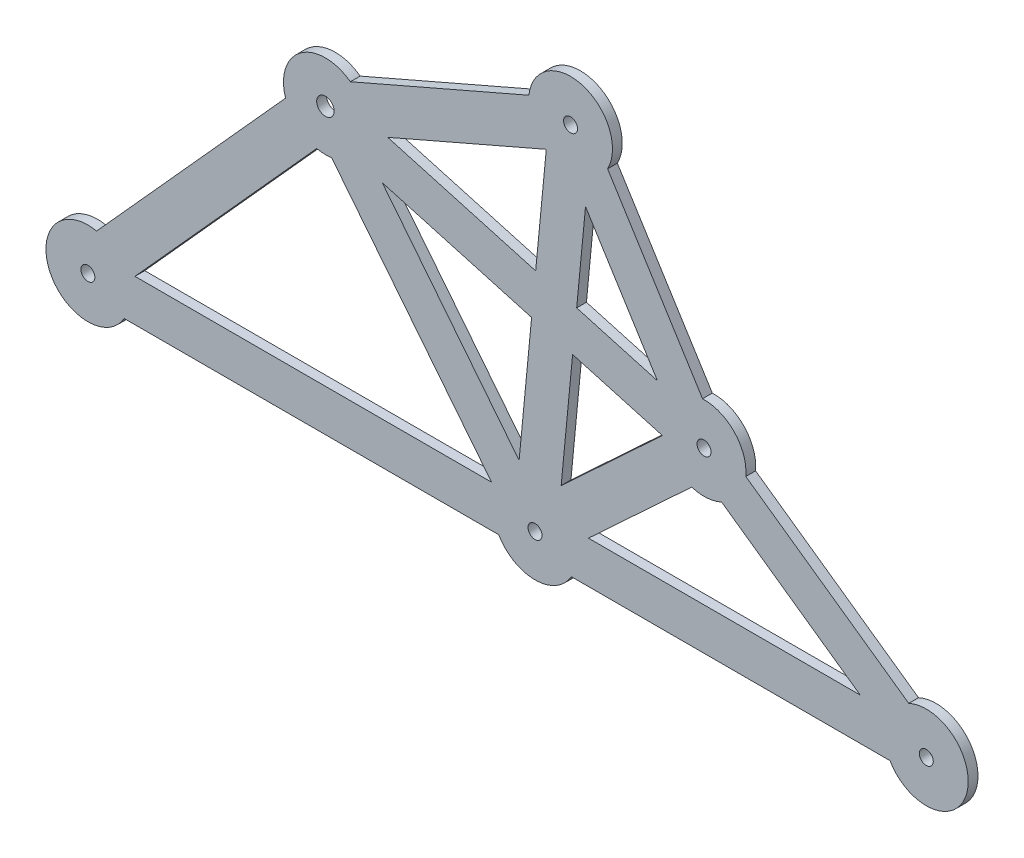
SolidWorks part; units mm, degrees
material "Cedar"
ref_plane "Front Plane" through (0, 0, 0) normal (0, 0, 1) x (1, 0, 0)
ref_plane "Top Plane" through (0, 0, 0) normal (0, 1, 0) x (1, 0, 0)
ref_plane "Right Plane" through (0, 0, 0) normal (1, 0, 0) x (0, 0, -1)
sketch "Sketch2" plane through (0, 0, 0) normal (0, 0, 1) x (1, 0, 0)
  line L1 (482.2677, -405.8805) -> (-152.7323, -405.8805)
  line L2 (482.2677, -405.8805) -> (482.2677, 229.1195)
  line L3 (482.2677, 229.1195) -> (-152.7323, 229.1195)
  line L4 (-152.7323, -405.8805) -> (-152.7323, 229.1195)
  line L5 (482.2677, -405.8805) -> (-152.7323, 229.1195) construction
  line L6 (482.2677, 229.1195) -> (-152.7323, -405.8805) construction
  point P0 (0, 0)
  dimension "D1" = 635
  dimension "D2" = 635
extrude "Boss-Extrude3" add sketch "Sketch2" along normal blind 4.445
sketch "Sketch3" plane through (0, 0, 0) normal (0, 0, -1) x (-1, 0, 0)
  circle A0 centre (-138.1432, 71.8714) radius 3.175
  circle A1 centre (-198.8095, -25.0001) radius 3.175
  circle A2 centre (-122.0047, -96.2659) radius 3.175
  circle A4 centre (-26.7547, 23.4697) radius 3.9751
  dimension "D1" = 6.35
  dimension "D2" = 6.35
  dimension "D3" = 6.35
  dimension "D5" = 7.9502
extrude "Cut-Extrude1" cut sketch "Sketch3" against normal through all
sketch "Sketch4" plane through (0, 0, 4.445) normal (0, 0, 1) x (1, 0, 0)
  line L0 (11.8465, 11.6102) -> (107.0965, -108.1254) construction
  line L1 (29.5712, 4.6291) -> (104.2799, -89.2848)
  line L2 (180.2372, -29.2393) -> (127.6196, -78.0622)
  line L3 (193.1946, -43.2038) -> (140.577, -92.0267)
  line L4 (154.9723, 62.9447) -> (198.1257, -5.9624)
  line L5 (138.827, 52.8336) -> (181.9805, -16.0735)
  line L6 (44.4794, 16.4886) -> (119.1881, -77.4253)
  line L7 (119.1804, 73.6915) -> (103.0418, -94.4458) construction
  line L8 (38.0897, 38.7805) -> (119.2162, 74.0324)
  line L9 (45.6817, 21.3087) -> (126.8082, 56.5606)
  line L10 (19.1626, 40.9415) -> (130.5512, 89.3432) construction
  line L11 (154.2884, 81.9824) -> (214.9548, -14.8891) construction
  line L12 (211.767, -38.9646) -> (134.9621, -110.2304) construction
  line L13 (127.0855, 56.3591) -> (114.0995, -78.9335)
  line L14 (146.0483, 54.539) -> (133.0624, -80.7536)
  line L15 (-152.7323, -405.8805) -> (482.2677, -405.8805) construction
  line L16 (31.9202, 41.806) -> (203.9751, -6.6638) construction
  line L17 (45.2171, 28.1644) -> (185.5126, -11.3585)
  line L18 (40.0516, 9.8281) -> (180.3471, -29.6948)
  line L19 (138.5024, -86.7409) -> (283.3069, -86.7409)
  line L20 (138.5024, -105.7909) -> (283.3069, -105.7909)
  line L21 (-64.6976, -86.7409) -> (105.5069, -86.7409)
  line L22 (-152.7323, 229.1195) -> (482.2677, 229.1195)
  line L23 (-152.7323, 229.1195) -> (-152.7323, -405.8805)
  line L24 (482.2677, 229.1195) -> (482.2677, -405.8805)
  line L25 (-152.7323, -405.8805) -> (482.2677, -405.8805)
  line L26 (-64.6976, -105.7909) -> (105.5069, -105.7909)
  line L27 (-95.344, -83.5098) -> (12.606, 36.2258) construction
  line L28 (-77.2226, -77.6347) -> (8.6332, 17.5946)
  line L29 (22.782, 4.8386) -> (-63.0739, -90.3908)
  line L30 (209.7928, -9.4351) -> (310.7879, -80.7008) construction
  line L31 (291.8166, -78.9716) -> (217.7809, -26.7294)
  line L32 (280.8333, -94.5366) -> (206.7976, -42.2944)
  circle A0 centre (26.7547, 23.4697) radius 19.05
  circle A1 centre (138.1432, 71.8714) radius 19.05
  circle A2 centre (198.8095, -25.0001) radius 19.05
  circle A3 centre (122.0047, -96.2659) radius 19.05
  circle A4 centre (-81.1953, -96.2659) radius 19.05
  circle A5 centre (299.8047, -96.2659) radius 19.05
  circle A6 centre (299.8047, -96.2659) radius 3.175
  circle A7 centre (-81.1953, -96.2659) radius 3.175
  circle A8 centre (122.0047, -96.2659) radius 3.175 construction
  dimension "D11" = 38.1
  dimension "D2" = 19.05
  dimension "D3" = 19.05
  dimension "D4" = 19.05
  dimension "D5" = 19.05
  dimension "D6" = 19.05
  dimension "D7" = 203.2
  dimension "D8" = 19.05
  dimension "D9" = 177.8
  dimension "D10" = 19.05
  dimension "D12" = 19.05
  dimension "D13" = 19.05
  dimension "D14" = 19.05
extrude "Cut-Extrude2" cut sketch "Sketch4" against normal through all
